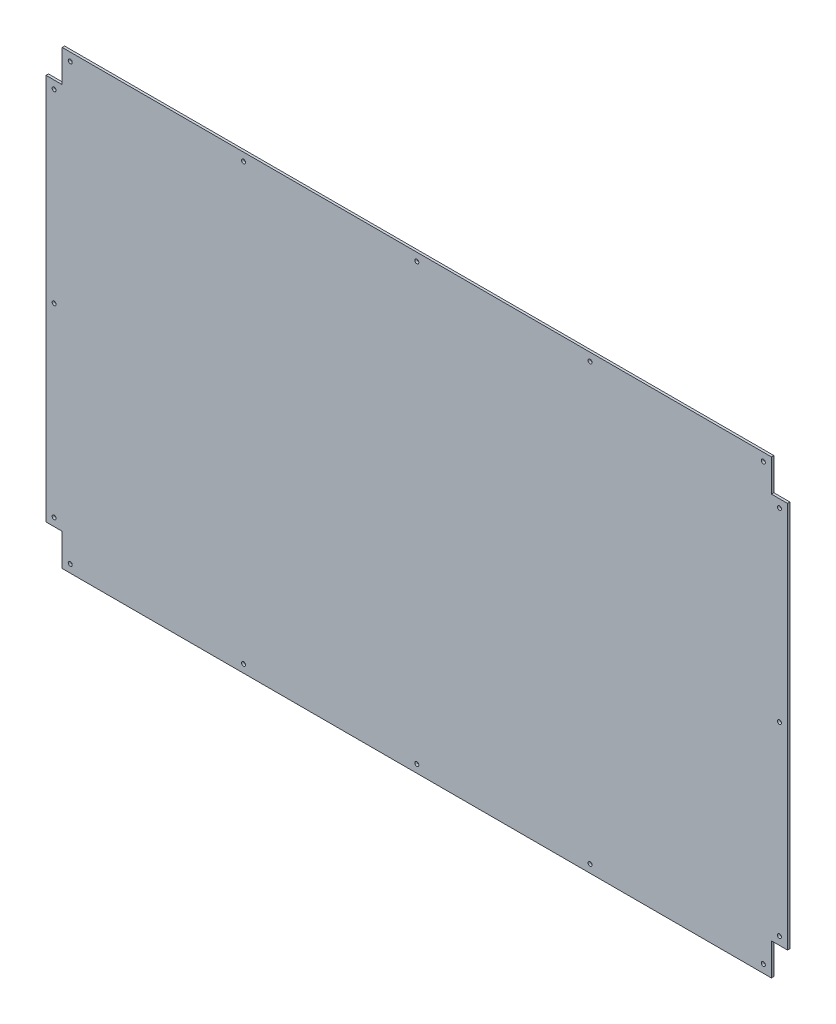
SolidWorks part; units mm, degrees
material "Acrylic (Medium-high impact)"
ref_plane "Front Plane" through (0, 0, 0) normal (0, 0, 1) x (1, 0, 0)
ref_plane "Top Plane" through (0, 0, 0) normal (0, 1, 0) x (1, 0, 0)
ref_plane "Right Plane" through (0, 0, 0) normal (1, 0, 0) x (0, 0, -1)
sketch "Sketch1" plane through (0, 0, 0) normal (0, 0, 1) x (1, 0, 0)
  line L1 (-389.6973, 339.1855) -> (490.3027, 339.1855)
  line L2 (-409.6973, 299.1855) -> (-409.6973, -180.8145)
  line L3 (-389.6973, -220.8145) -> (490.3027, -220.8145)
  line L4 (510.3027, 299.1855) -> (510.3027, -180.8145)
  line L7 (-409.6973, 299.1855) -> (-389.6973, 299.1855)
  line L8 (-389.6973, 339.1855) -> (-389.6973, 299.1855)
  line L9 (490.3027, 339.1855) -> (490.3027, 299.1855)
  line L10 (490.3027, 299.1855) -> (510.3027, 299.1855)
  line L12 (490.3027, -180.8145) -> (510.3027, -180.8145)
  line L13 (490.3027, -180.8145) -> (490.3027, -220.8145)
  line L16 (-409.6973, -180.8145) -> (-389.6973, -180.8145)
  line L19 (-389.6973, -180.8145) -> (-389.6973, -220.8145)
  dimension "D2" = 480
  dimension "D3" = 20
  dimension "D4" = 40
  dimension "D5" = 880
  dimension "D7" = 20
  dimension "D8" = 40
  dimension "D9" = 20
  dimension "D10" = 40
  dimension "D13" = 20
  dimension "D14" = 40
extrude "Boss-Extrude1" add sketch "Sketch1" along normal blind 3
sketch "Sketch2" plane through (0, 0, 3) normal (0, 0, 1) x (1, 0, 0)
  line L0 (490.3027, 339.1855) -> (-389.6973, 339.1855) construction
  line L1 (-389.6973, 339.1855) -> (-389.6973, 299.1855) construction
  line L2 (490.3027, 299.1855) -> (490.3027, 339.1855) construction
  line L3 (-389.6973, -220.8145) -> (490.3027, -220.8145) construction
  line L4 (-389.6973, -180.8145) -> (-389.6973, -220.8145) construction
  line L5 (490.3027, -220.8145) -> (490.3027, -180.8145) construction
  line L7 (-389.6973, 299.1855) -> (-409.6973, 299.1855) construction
  line L8 (-409.6973, 299.1855) -> (-409.6973, -180.8145) construction
  line L9 (-409.6973, -180.8145) -> (-389.6973, -180.8145) construction
  line L10 (510.3027, 299.1855) -> (490.3027, 299.1855) construction
  line L11 (510.3027, -180.8145) -> (510.3027, 299.1855) construction
  line L12 (490.3027, -180.8145) -> (510.3027, -180.8145) construction
  circle A0 centre (-379.6973, 329.1855) radius 2.5
  circle A1 centre (480.3027, 329.1855) radius 2.5
  circle A2 centre (-164.6973, 329.1855) radius 2.5
  circle A3 centre (50.3027, 329.1855) radius 2.5
  circle A4 centre (265.3027, 329.1855) radius 2.5
  circle A5 centre (-379.6973, -210.8145) radius 2.5
  circle A6 centre (480.3027, -210.8145) radius 2.5
  circle A7 centre (265.3027, -210.8145) radius 2.5
  circle A8 centre (50.3027, -210.8145) radius 2.5
  circle A10 centre (-164.6973, -210.8145) radius 2.5
  circle A11 centre (-399.6973, 289.1855) radius 2.5
  circle A12 centre (-399.6973, -170.8145) radius 2.5
  circle A13 centre (-399.6973, 59.1855) radius 2.5
  circle A14 centre (500.3027, 289.1855) radius 2.5
  circle A15 centre (500.3027, 59.1855) radius 2.5
  circle A16 centre (500.3027, -170.8145) radius 2.5
  point P30 (0, 0)
  dimension "D1" = 5
  dimension "D3" = 10
  dimension "D4" = 10
  dimension "D8" = 10
  dimension "D13" = 10
  dimension "D14" = 10
  dimension "D15" = 10
  dimension "D17" = 10
  dimension "D19" = 10
  dimension "D20" = 10
  dimension "D21" = 10
  dimension "D23" = 10
  dimension "D24" = 10
  dimension "D25" = 10
  dimension "D27" = 10
  dimension "D28" = 10
  dimension "D31" = 10
  dimension "D32" = 10
  dimension "D33" = 10
  dimension "D2" = 10
  dimension "D5" = 10
  dimension "D6" = 215
  dimension "D7" = 10
  dimension "D9" = 215
  dimension "D10" = 215
  dimension "D11" = 10
  dimension "D12" = 10
  dimension "D16" = 215
  dimension "D18" = 215
  dimension "D22" = 215
  dimension "D26" = 230
  dimension "D29" = 10
  dimension "D30" = 230
extrude "Cut-Extrude1" cut sketch "Sketch2" against normal through all
